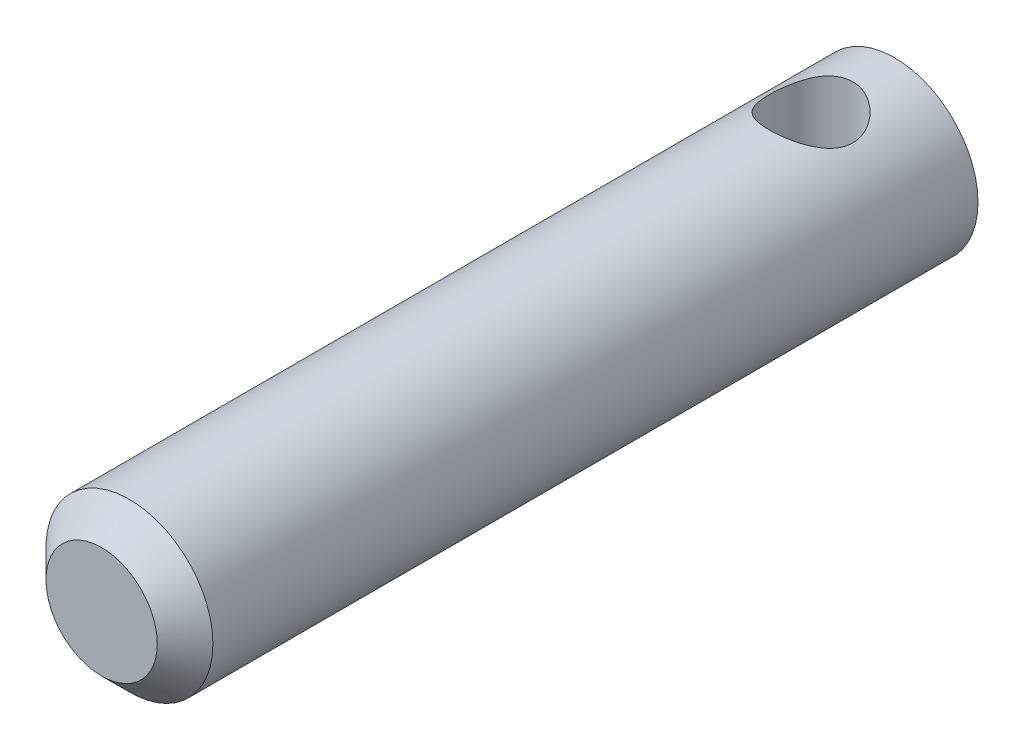
SolidWorks part; units mm, degrees
material "1.5805 (10NiCr5-4)"
ref_plane "Plan de face" through (0, 0, 0) normal (0, 0, 1) x (1, 0, 0)
ref_plane "Plan de dessus" through (0, 0, 0) normal (0, 1, 0) x (1, 0, 0)
ref_plane "Plan de droite" through (0, 0, 0) normal (1, 0, 0) x (0, 0, -1)
sketch "Esquisse1" plane through (0, 0, 0) normal (0, 0, 1) x (1, 0, 0)
  circle A0 centre (0, 0) radius 3
  dimension "D1" = 6
extrude "Boss.-Extru.1" add sketch "Esquisse1" along normal blind 28.5
sketch "Esquisse2" plane through (0, 0, 0) normal (0, 1, 0) x (1, 0, 0)
  line L0 (3, 0) -> (-3, 0) construction
  circle A0 centre (0, -3) radius 1.5
  dimension "D1" = 3
  dimension "D2" = 3
  dimension "D3" = 0
extrude "Enlèv. mat.-Extru.1" cut sketch "Esquisse2" against normal through all both and the other way through all
chamfer "Chanfrein1" distance 1 angle 45 1 edges at (3, 0, 28.5)
